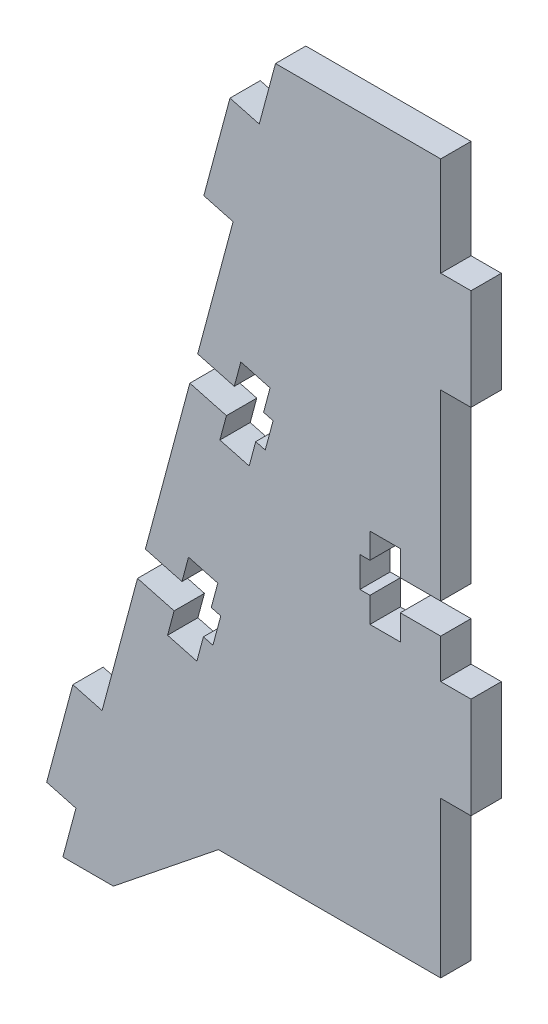
SolidWorks part; units mm, degrees
material "Balsa"
ref_plane "Alzado" through (0, 0, 0) normal (0, 0, 1) x (1, 0, 0)
ref_plane "Planta" through (0, 0, 0) normal (0, 1, 0) x (1, 0, 0)
ref_plane "Vista lateral" through (0, 0, 0) normal (1, 0, 0) x (0, 0, -1)
sketch "Croquis1" plane through (0, 0, 0) normal (0, 0, 1) x (1, 0, 0)
  line L8 (484.8557, 82.973) -> (491.2152, 82.973)
  line L11 (480.6618, 67.3211) -> (477.764, 68.0975)
  line L12 (480.3522, 77.7568) -> (483.25, 76.9803)
  line L13 (465.1089, 9.2769) -> (462.2111, 10.0533)
  line L14 (464.7993, 19.7126) -> (467.6971, 18.9361)
  line L15 (483.25, 76.9803) -> (484.8557, 82.973)
  line L16 (480.6618, 67.3211) -> (477.1559, 54.2367)
  line L17 (476.3794, 51.339) -> (471.9795, 34.9182)
  line L18 (471.203, 32.0205) -> (467.6971, 18.9361)
  line L20 (494.8557, 12.7731) -> (479.2056, 12.7731)
  line L21 (465.1089, 9.2769) -> (463.8148, 4.4472)
  line L22 (463.8148, 4.4472) -> (468.8148, 4.4472)
  line L23 (468.8148, 4.4472) -> (479.2056, 12.7731)
  line L25 (494.8557, 12.7731) -> (501.2056, 12.7731)
  line L26 (480.7777, 53.2663) -> (477.1559, 54.2367)
  line L27 (484.323, 54.9049) -> (481.4249, 55.6815)
  line L28 (482.8994, 49.5919) -> (482.2523, 47.1771)
  line L29 (482.2523, 47.1771) -> (479.3542, 47.9537)
  line L30 (480.7777, 53.2663) -> (481.4249, 55.6815)
  line L31 (483.6759, 52.4897) -> (484.323, 54.9049)
  line L32 (484.6176, 52.2374) -> (483.6759, 52.4897)
  line L33 (480.0013, 50.3685) -> (479.3542, 47.9537)
  line L34 (483.8412, 49.3396) -> (482.8994, 49.5919)
  line L35 (476.3794, 51.339) -> (480.0013, 50.3685)
  line L36 (484.6176, 52.2374) -> (483.8412, 49.3396)
  line L37 (475.6014, 33.9477) -> (471.9795, 34.9182)
  line L38 (479.1466, 35.5864) -> (476.2485, 36.363)
  line L39 (477.723, 30.2734) -> (477.076, 27.8586)
  line L40 (477.076, 27.8586) -> (474.1779, 28.6352)
  line L41 (475.6014, 33.9477) -> (476.2485, 36.363)
  line L42 (478.4995, 33.1712) -> (479.1466, 35.5864)
  line L43 (479.4413, 32.9189) -> (478.4995, 33.1712)
  line L44 (474.8249, 31.05) -> (474.1779, 28.6352)
  line L45 (478.6648, 30.0211) -> (477.723, 30.2734)
  line L46 (471.203, 32.0205) -> (474.8249, 31.05)
  line L47 (479.4413, 32.9189) -> (478.6648, 30.0211)
  line L59 (501.2056, 12.7731) -> (501.2056, 28.1731)
  line L60 (501.2056, 28.1731) -> (504.2056, 28.1731)
  line L61 (504.2056, 28.1731) -> (504.2056, 38.1731)
  line L62 (504.2056, 38.1731) -> (501.2056, 38.1731)
  line L63 (501.2056, 38.1731) -> (501.2056, 42.0731)
  line L64 (501.2056, 63.1731) -> (504.2056, 63.1731)
  line L65 (504.2056, 63.1731) -> (504.2056, 73.1731)
  line L66 (504.2056, 73.1731) -> (501.2056, 73.1731)
  line L67 (501.2056, 73.1731) -> (501.2056, 82.973)
  line L68 (501.2056, 82.973) -> (491.2152, 82.973)
  line L69 (501.2056, 43.5731) -> (488.6228, 43.5731) construction
  line L70 (501.2056, 45.0731) -> (497.2056, 45.0731)
  line L72 (501.2056, 42.0731) -> (497.2056, 42.0731)
  line L73 (493.2056, 45.0731) -> (493.2056, 42.0731)
  line L74 (497.2056, 47.5731) -> (494.2056, 47.5731)
  line L75 (497.2056, 47.5731) -> (497.2056, 45.0731)
  line L76 (497.2056, 39.5731) -> (494.2056, 39.5731)
  line L77 (494.2056, 47.5731) -> (494.2056, 45.0731)
  line L78 (501.2056, 45.0731) -> (501.2056, 63.1731)
  line L79 (497.2056, 42.0731) -> (497.2056, 39.5731)
  line L80 (494.2056, 45.0731) -> (493.2056, 45.0731)
  line L81 (494.2056, 42.0731) -> (493.2056, 42.0731)
  line L82 (494.2056, 42.0731) -> (494.2056, 39.5731)
  line L116 (480.3522, 77.7568) -> (477.764, 68.0975)
  line L117 (464.7993, 19.7126) -> (462.2111, 10.0533)
  dimension "D1" = 70.1999
  dimension "D2" = 25
  dimension "D3" = 10
  dimension "D4" = 3
  dimension "D5" = 3
  dimension "D6" = 3
  dimension "D7" = 10
  dimension "D8" = 3
  dimension "D9" = 15.4
  dimension "D10" = 22
  dimension "D11" = 3
  dimension "D12" = 1.5
  dimension "D13" = 4
  dimension "D14" = 8
  dimension "D15" = 3
  dimension "D16" = 1
  dimension "D17" = 5.4
  dimension "D18" = 8
extrude "Saliente-Extruir1" add sketch "Croquis1" along normal mid plane 3
